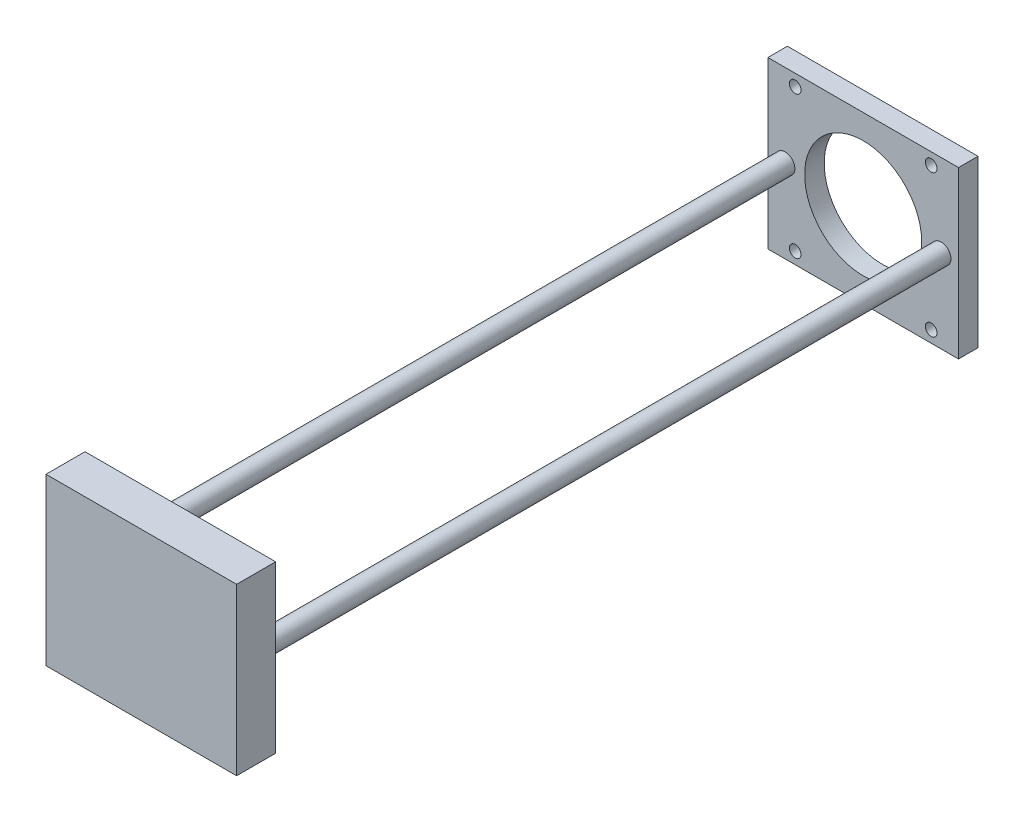
SolidWorks part; units mm, degrees
ref_plane "Alzado" through (0, 0, 0) normal (0, 0, 1) x (1, 0, 0)
ref_plane "Planta" through (0, 0, 0) normal (0, 1, 0) x (1, 0, 0)
ref_plane "Vista lateral" through (0, 0, 0) normal (1, 0, 0) x (0, 0, -1)
sketch "Croquis1" plane through (0, 0, 0) normal (0, 0, 1) x (1, 0, 0)
  line L0 (-34.85, 42.5) -> (-34.85, 36.5) construction
  line L1 (48.85, -42.5) -> (-48.85, -42.5)
  line L2 (48.85, -42.5) -> (48.85, 42.5)
  line L3 (48.85, 42.5) -> (-48.85, 42.5)
  line L4 (-48.85, -42.5) -> (-48.85, 42.5)
  line L5 (48.85, -42.5) -> (-48.85, 42.5) construction
  line L6 (48.85, 42.5) -> (-48.85, -42.5) construction
  line L7 (-34.85, 36.5) -> (-48.85, 36.5) construction
  line L8 (0, 42.5) -> (0, -42.5) construction
  line L9 (-48.85, 0) -> (48.85, 0) construction
  circle A0 centre (-34.85, 36.5) radius 3
  circle A1 centre (0, 0) radius 30
  circle A2 centre (34.85, 36.5) radius 3
  circle A3 centre (34.85, -36.5) radius 3
  circle A4 centre (-34.85, -36.5) radius 3
  point P0 (0, 0)
  dimension "D5" = 6
  dimension "D6" = 60
  dimension "D1" = 97.7
  dimension "D2" = 85
  dimension "D3" = 6
  dimension "D4" = 14
extrude "Saliente-Extruir1" add sketch "Croquis1" along normal blind 10
sketch "Croquis2" plane through (0, 0, 10) normal (0, 0, 1) x (1, 0, 0)
  line L0 (-34.85, 36.5) -> (-34.85, -36.5) construction
  line L1 (34.85, 36.5) -> (34.85, -36.5) construction
  line L3 (0, 42.5) -> (0, -42.5) construction
  line L4 (48.85, 42.5) -> (-48.85, 42.5) construction
  line L5 (-48.85, -42.5) -> (48.85, -42.5) construction
  circle A1 centre (-40, 0) radius 5
  circle A2 centre (40, 0) radius 5
  point P15 (0, 0)
  dimension "D1" = 10
  dimension "D2" = 40
extrude "Saliente-Extruir2" add sketch "Croquis2" along normal blind 350
ref_plane "Plano1" through (0, 0, 360) normal (0, 0, 1) x (1, 0, 0)
sketch "Croquis3" plane through (0, 0, 360) normal (0, 0, 1) x (1, 0, 0)
  line L1 (-48.85, 42.5) -> (48.85, 42.5)
  line L2 (-48.85, 42.5) -> (-48.85, -42.5)
  line L3 (-48.85, -42.5) -> (48.85, -42.5)
  line L4 (48.85, 42.5) -> (48.85, -42.5)
extrude "Saliente-Extruir3" add sketch "Croquis3" along normal blind 20
